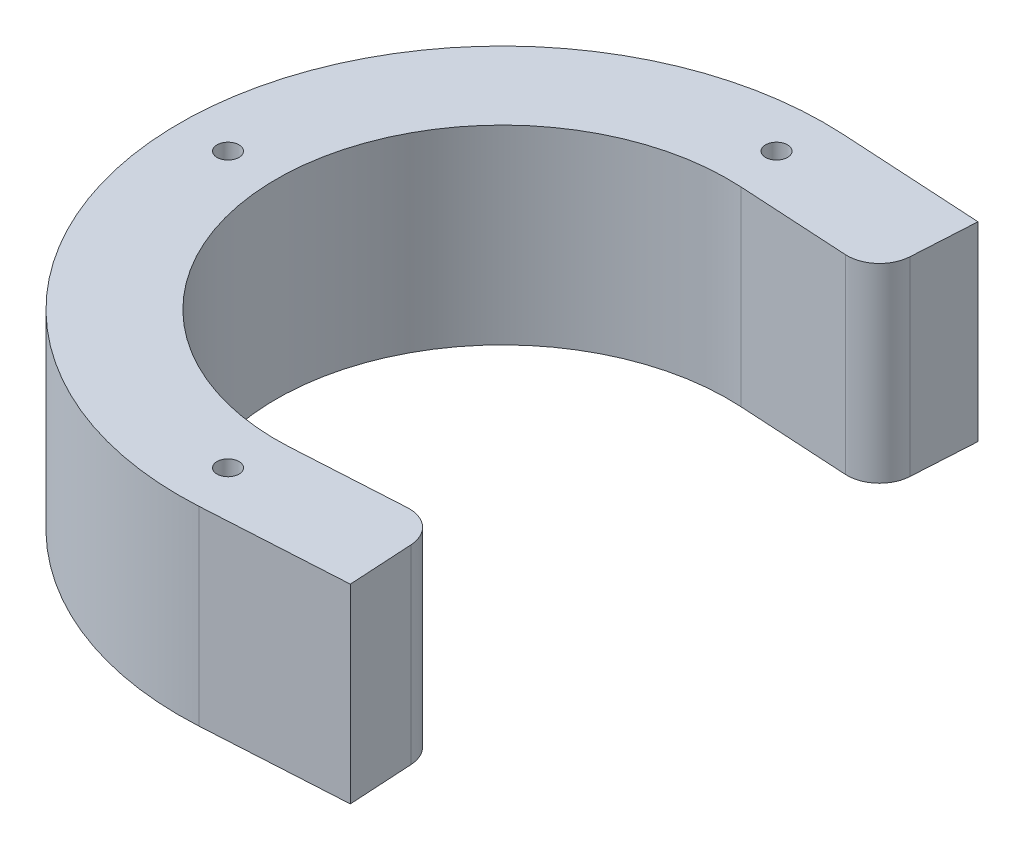
SolidWorks part; units mm, degrees
material "PA Type 6"
ref_plane "Front Plane" through (0, 0, 0) normal (0, 0, 1) x (1, 0, 0)
ref_plane "Top Plane" through (0, 0, 0) normal (0, 1, 0) x (1, 0, 0)
ref_plane "Right Plane" through (0, 0, 0) normal (1, 0, 0) x (0, 0, -1)
sketch "Sketch2" plane through (0, 0, 0) normal (0, 1, 0) x (1, 0, 0)
  line L0 (0, 0) -> (-42.5, 0) construction
  line L1 (2.8869, 49.9166) -> (25.0869, 48.6327)
  line L2 (2.0208, 34.9416) -> (24.2208, 33.6577)
  line L3 (24.2208, 33.6577) -> (25.0869, 48.6327)
  line L4 (2.8869, -49.9166) -> (25.0869, -48.6327)
  line L5 (2.0208, -34.9416) -> (24.2208, -33.6577)
  line L6 (24.2208, -33.6577) -> (25.0869, -48.6327)
  arc A0 (2.8869, 49.9166) -> (2.8869, -49.9166) centre (0, 0) ccw
  arc A1 (2.0208, 34.9416) -> (2.0208, -34.9416) centre (0, 0) ccw
  circle A2 centre (0, 0) radius 42.5 construction
  circle A6 centre (-42.5, 0) radius 1.7
  circle A8 centre (0, 42.5) radius 1.7
  circle A9 centre (0, -42.5) radius 1.7
  dimension "D1" = 7.5
  dimension "D2" = 35
  dimension "D3" = 85
  dimension "D4" = 3.31
  dimension "D6" = 3.4
  dimension "D5" = 22.2
extrude "Boss-Extrude1" add sketch "Sketch2" along normal blind 29.5
sketch "Sketch3" plane through (0, 29.5, 0) normal (0, 1, 0) x (1, 0, 0)
  line L0 (0, 0) -> (-42.5, 0) construction
  line L1 (-40.0251, 2.4749) -> (-48.7333, 11.1831)
  line L2 (-40.0251, -2.4749) -> (-48.7333, -11.1831)
  line L3 (-2.4749, 40.0251) -> (-11.1831, 48.7333)
  line L4 (2.4749, 40.0251) -> (11.8481, 49.3983)
  line L5 (25.0869, 48.6327) -> (2.8869, 49.9166) construction
  line L6 (0, 0) -> (0, 42.5) construction
  arc A1 (-40.0251, -2.4749) -> (-40.0251, 2.4749) centre (-42.5, 0) ccw
  arc A3 (2.0208, 34.9416) -> (2.0208, -34.9416) centre (0, 0) ccw construction
  arc A6 (2.8869, 49.9166) -> (2.8869, -49.9166) centre (0, 0) ccw construction
  arc A7 (2.8869, 49.9166) -> (2.8869, -49.9166) centre (0, 0) ccw
  arc A8 (2.0208, 34.9416) -> (2.0208, -34.9416) centre (0, 0) ccw
  arc A9 (2.4749, 40.0251) -> (-2.4749, 40.0251) centre (0, 42.5) cw
  dimension "D1" = 7
  dimension "D2" = 90
fillet "Fillet2" radius 5 2 edges at (24.2208, 14.75, 33.6577) (24.2208, 14.75, -33.6577)
